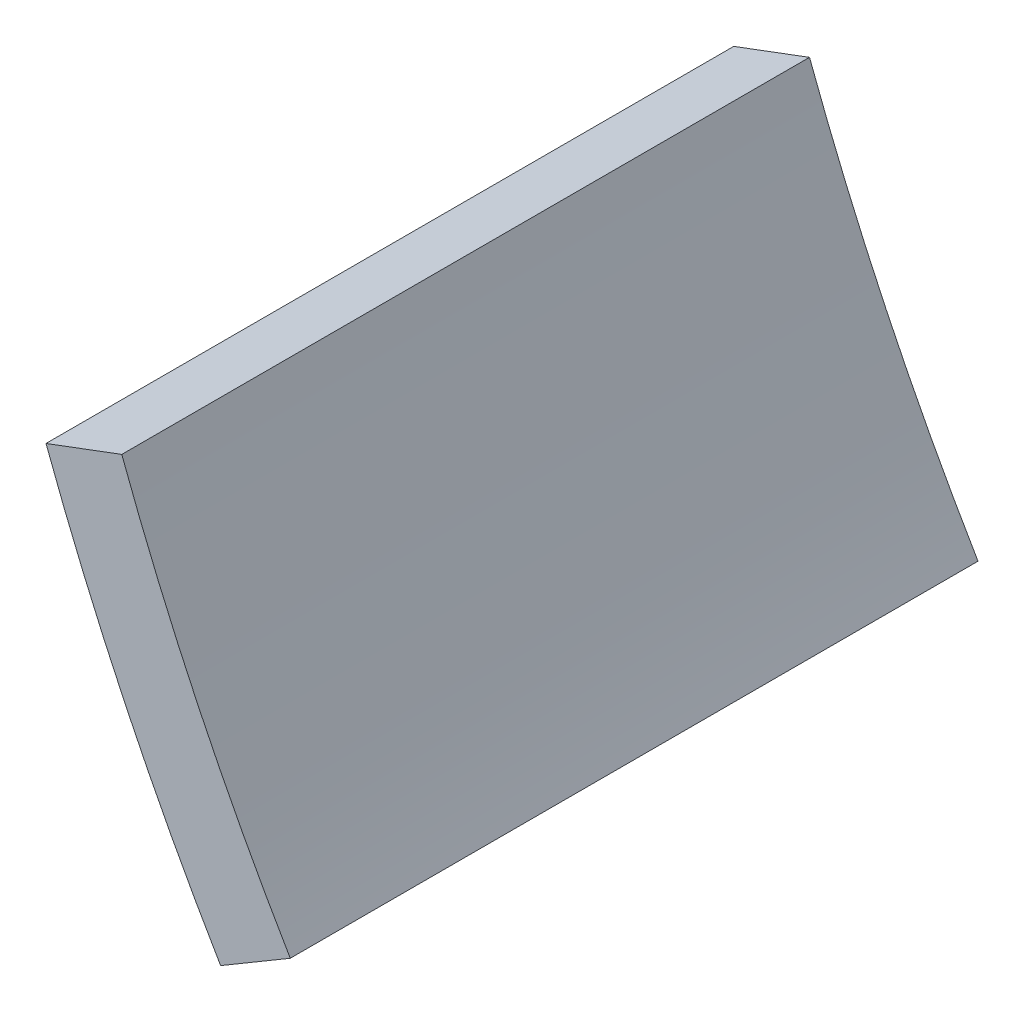
SolidWorks part; units mm, degrees
ref_plane "Plan de face" through (0, 0, 0) normal (0, 0, 1) x (1, 0, 0)
ref_plane "Plan de dessus" through (0, 0, 0) normal (0, 1, 0) x (1, 0, 0)
ref_plane "Plan de droite" through (0, 0, 0) normal (1, 0, 0) x (0, 0, -1)
sketch "Esquisse1" plane through (0, 0, 0) normal (0, 0, 1) x (1, 0, 0)
  line L0 (0, 0) -> (-58.607, -21.9571) construction
  line L1 (0, 0) -> (-56.1442, -33.208) construction
  line L2 (-51.504, -19.296) -> (-53.3769, -19.9977)
  line L3 (-47.3392, -28) -> (-49.0606, -29.0182)
  arc A0 (-47.3392, -28) -> (-51.504, -19.296) centre (0, 0) cw
  arc A1 (-49.0606, -29.0182) -> (-53.3769, -19.9977) centre (0, 0) cw
  dimension "D3" = 55
  dimension "D1" = 10
  dimension "D2" = 2
  dimension "D4" = 28
extrude "Boss.-Extru.1" add sketch "Esquisse1" along normal blind 17
